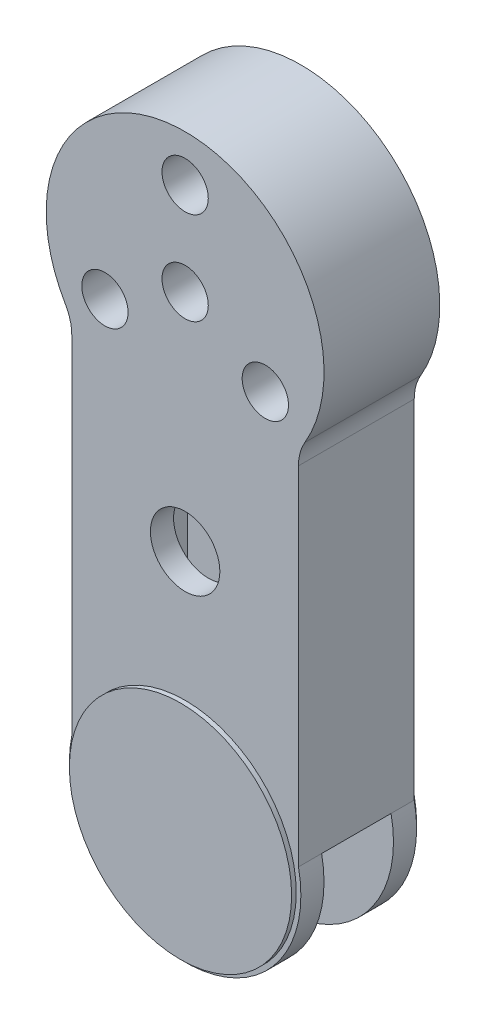
SolidWorks part; units mm, degrees
ref_plane "Plan de face" through (0, 0, 0) normal (0, 0, 1) x (1, 0, 0)
ref_plane "Plan de dessus" through (0, 0, 0) normal (0, 1, 0) x (1, 0, 0)
ref_plane "Plan de droite" through (0, 0, 0) normal (1, 0, 0) x (0, 0, -1)
sketch "Esquisse1" plane through (0, 0, 0) normal (0, 0, 1) x (1, 0, 0)
  line L0 (48.9616, -40.55) -> (48.9616, -190.5831)
  line L2 (-48.9616, -40.55) -> (-48.9616, -190.5831)
  arc A0 (51.7212, -30.4125) -> (-51.7212, -30.4125) centre (0, 0) ccw
  arc A1 (-51.7212, -30.4125) -> (-48.9616, -40.55) centre (-68.9616, -40.55) cw
  arc A2 (51.7212, -30.4125) -> (48.9616, -40.55) centre (68.9616, -40.55) ccw
  arc A5 (48.9616, -190.5831) -> (-48.9616, -190.5831) centre (0, -200.7204) cw
  dimension "D1" = 20
  dimension "D2" = 60
extrude "Boss.-Extru.1" add sketch "Esquisse1" along normal mid plane 50
sketch "Esquisse6" plane through (0, 0, 0) normal (0, 0, 1) x (1, 0, 0)
  line L0 (-48.9616, -190.5831) -> (-44.8194, -186.441)
  line L1 (48.9616, -190.5831) -> (84.8715, -248.5477)
  line L2 (44.8194, -186.441) -> (48.9616, -190.5831)
  line L3 (84.8715, -248.5477) -> (0, -290.8515)
  line L4 (0, -290.8515) -> (-95.2339, -248.5477)
  line L5 (-48.9616, -190.5831) -> (-95.2339, -248.5477)
  line L8 (38.9616, -172.2989) -> (38.9616, -60.55)
  line L9 (-28.9616, -50.55) -> (28.9616, -50.55)
  line L10 (-38.9616, -172.2989) -> (-38.9616, -60.55)
  arc A0 (38.9616, -60.55) -> (28.9616, -50.55) centre (28.9616, -60.55) ccw
  arc A1 (44.8194, -186.441) -> (38.9616, -172.2989) centre (58.9616, -172.2989) cw
  arc A2 (-38.9616, -172.2989) -> (-44.8194, -186.441) centre (-58.9616, -172.2989) cw
  arc A3 (-38.9616, -60.55) -> (-28.9616, -50.55) centre (-28.9616, -60.55) cw
  arc A4 (-48.9616, -190.5831) -> (48.9616, -190.5831) centre (0, -200.7204) ccw construction
  dimension "D1" = 10
  dimension "D2" = 20
extrude "Enlèv. mat.-Extru.6" cut sketch "Esquisse6" against normal mid plane 30
sketch "Esquisse7" plane through (0, 0, 25) normal (0, 0, 1) x (1, 0, 0)
  line L2 (0, 0) -> (0, 40)
  circle A0 centre (0, 0) radius 10
  circle A1 centre (0, 40) radius 10
  circle A2 centre (34.641, -20) radius 10
  circle A3 centre (-34.641, -20) radius 10
  dimension "D1" = 40
  dimension "D2" = 40
  dimension "D3" = 40
extrude "Enlèv. mat.-Extru.7" cut sketch "Esquisse7" against normal through all
sketch "Esquisse8" plane through (0, 0, 25) normal (0, 0, 1) x (1, 0, 0)
  circle A0 centre (0, -200.7204) radius 48
extrude "Boss.-Extru.2" add sketch "Esquisse8" along normal blind 2
sketch "Esquisse9" plane through (0, 0, -25) normal (0, 0, -1) x (-1, 0, 0)
  circle A0 centre (0, -200.7204) radius 48
extrude "Boss.-Extru.3" add sketch "Esquisse9" along normal blind 2
sketch "Esquisse11" plane through (0, 0, 25) normal (0, 0, 1) x (1, 0, 0)
  circle A0 centre (0, -97.0612) radius 15
extrude "Enlèv. mat.-Extru.8" cut sketch "Esquisse11" against normal blind 20
sketch "Esquisse12" plane through (0, 0, -15) normal (0, 0, 1) x (1, 0, 0)
  circle A0 centre (0, -200.7204) radius 10
extrude "Boss.-Extru.4" add sketch "Esquisse12" along normal up to surface (30 mm away) up to face at (-15, -97.0612, 15)
